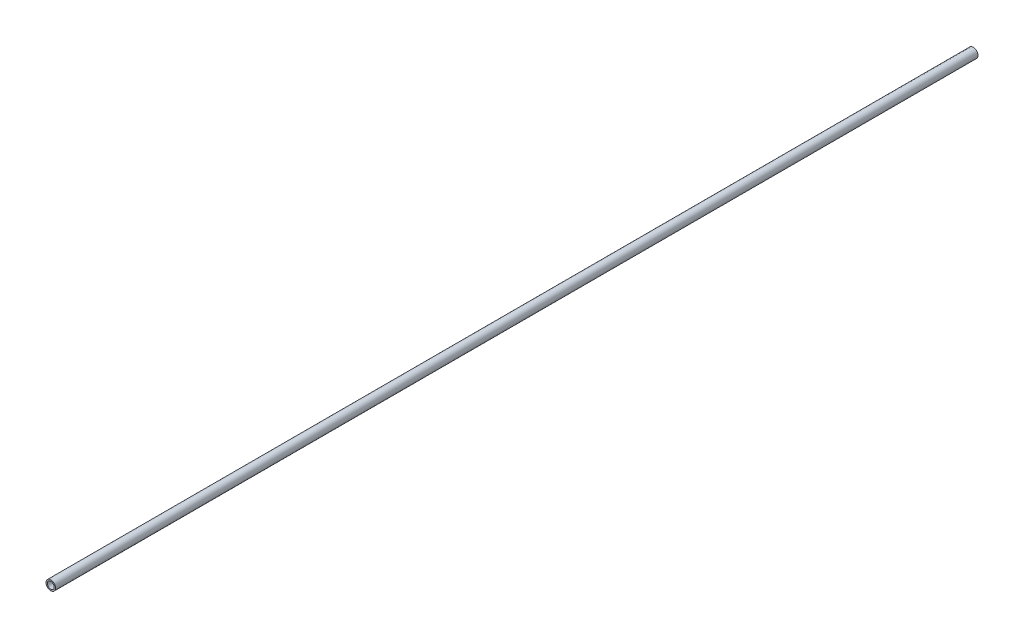
SolidWorks part; units mm, degrees
ref_plane "Front Plane" through (0, 0, 0) normal (0, 0, 1) x (1, 0, 0)
ref_plane "Top Plane" through (0, 0, 0) normal (0, 1, 0) x (1, 0, 0)
ref_plane "Right Plane" through (0, 0, 0) normal (1, 0, 0) x (0, 0, -1)
sketch "Sketch2" plane through (0, 0, 0) normal (0, 0, 1) x (1, 0, 0)
  circle A0 centre (0, 0) radius 1.25
  circle A1 centre (0, 0) radius 1.75
  dimension "D1" = 2.5
  dimension "D2" = 3.5
extrude "Boss-Extrude1" add sketch "Sketch2" against normal blind 340
